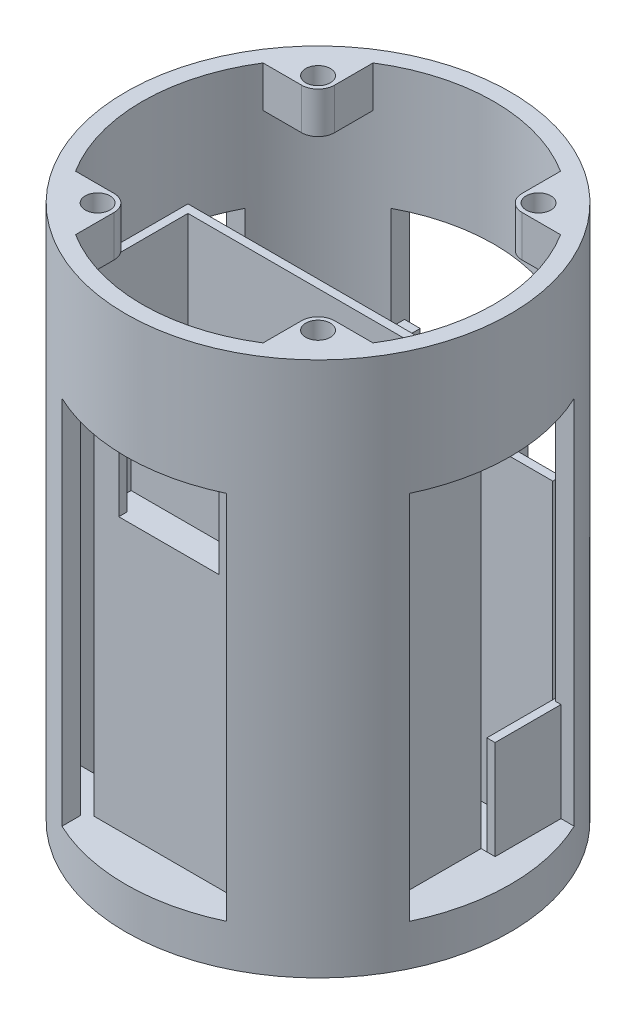
SolidWorks part; units mm, degrees
ref_plane "Plan de face" through (0, 0, 0) normal (0, 0, 1) x (1, 0, 0)
ref_plane "Plan de dessus" through (0, 0, 0) normal (0, 1, 0) x (1, 0, 0)
ref_plane "Plan de droite" through (0, 0, 0) normal (1, 0, 0) x (0, 0, -1)
sketch "Esquisse1" plane through (0, 0, 0) normal (0, 1, 0) x (1, 0, 0)
  circle A0 centre (0, 0) radius 23.35
  dimension "D1" = 46.7
extrude "Boss.-Extru.1" add sketch "Esquisse1" along normal blind 5
sketch "Esquisse2" plane through (0, 5, 0) normal (0, 1, 0) x (1, 0, 0)
  line L1 (-18.5, 10) -> (18.5, 10)
  line L2 (-18.5, 10) -> (-18.5, 2)
  line L3 (-18.5, 2) -> (18.5, 2)
  line L4 (18.5, 10) -> (18.5, 2)
  line L5 (-16.8, 1) -> (16.8, 1)
  line L6 (-16.8, 1) -> (-16.8, -13.6)
  line L7 (-16.8, -13.6) -> (16.8, -13.6)
  line L8 (16.8, 1) -> (16.8, -13.6)
  dimension "D1" = 8
  dimension "D2" = 37
  dimension "D3" = 18.5
  dimension "D4" = 2
  dimension "D5" = 14.6
  dimension "D6" = 33.6
  dimension "D7" = 16.8
  dimension "D8" = 1
extrude "Enlèv. mat.-Extru.4" cut sketch "Esquisse2" against normal blind 3
sketch "Esquisse10" plane through (0, 5, 0) normal (0, 1, 0) x (1, 0, 0)
  circle A0 centre (0, 0) radius 21.35
  circle A1 centre (0, 0) radius 23.35 construction
  circle M2 centre (0, 0) radius 23.35
  line M8 (16.8, 1) -> (16.8, -13.6)
  line M9 (16.8, -13.6) -> (-16.8, -13.6)
  line M10 (-16.8, -13.6) -> (-16.8, 1)
  dimension "D1" = 2
extrude "Boss.-Extru.2" add sketch "Esquisse10" along normal blind 60 contours A0 M2 M8 M9 M10
sketch "Esquisse11" plane through (0, 0, 0) normal (0, 0, 1) x (1, 0, 0)
  line L0 (-23.35, 0) -> (23.35, 0) construction
  line L1 (-10, 5) -> (10, 5)
  line L2 (-10, 5) -> (-10, 50)
  line L3 (-10, 50) -> (10, 50)
  line L4 (10, 5) -> (10, 50)
  line L5 (23.35, 65) -> (-23.35, 65) construction
  dimension "D1" = 5
  dimension "D2" = 15
  dimension "D3" = 10
  dimension "D4" = 20
extrude "Enlèv. mat.-Extru.5" cut sketch "Esquisse11" against normal through all both and the other way through all
sketch "Esquisse12" plane through (0, 0, 0) normal (1, 0, 0) x (0, 0, -1)
  line L0 (23.35, 65) -> (-23.35, 65) construction
  line L1 (-10, 50) -> (10, 50)
  line L2 (-10, 50) -> (-10, 5)
  line L3 (-10, 5) -> (10, 5)
  line L4 (10, 50) -> (10, 5)
  line L5 (-23.35, 0) -> (23.35, 0) construction
  dimension "D1" = 20
  dimension "D2" = 15
  dimension "D3" = 5
  dimension "D4" = 10
extrude "Enlèv. mat.-Extru.6" cut sketch "Esquisse12" against normal through all both and the other way through all
sketch "Esquisse13" plane through (0, 5, 0) normal (0, 1, 0) x (1, 0, 0)
  line L0 (-17.8, 2) -> (-17.8, -11.7891)
  line L1 (-18.5, 2) -> (18.5, 2) construction
  line L2 (17.8, 2) -> (17.8, -11.7891)
  line L3 (-16.8, 1) -> (-16.8, -13.6) construction
  line L4 (16.8, 1) -> (16.8, -13.1751) construction
  line L5 (-16.4579, -13.6) -> (16.4579, -13.6) construction
  line L6 (-8.1, -14.6) -> (8.1, -14.6)
  line L7 (-8.1, -14.6) -> (-8.1, -17.1)
  line L8 (-8.1, -17.1) -> (8.1, -17.1)
  line L9 (8.1, -14.6) -> (8.1, -17.1)
  line L10 (-9.1, -13.6) -> (9.1, -13.6)
  line L11 (-9.1, -13.6) -> (-9.1, -18.1)
  line L12 (-9.1, -18.1) -> (9.1, -18.1)
  line L13 (9.1, -13.6) -> (9.1, -18.1)
  arc A0 (-18.8633, -10) -> (-16.8, -13.1751) centre (0, 0) ccw construction
  arc A1 (16.8, -13.1751) -> (18.8633, -10) centre (0, 0) ccw construction
  point P26 (9.1, -15.85)
  point P27 (8.1, -15.85)
  line M14 (18.5, 2) -> (-18.5, 2)
  arc M15 (16.8, -13.1751) -> (18.8633, -10) centre (0, 0) ccw
  arc M27 (-18.8633, -10) -> (-16.8, -13.1751) centre (0, 0) ccw
  line M28 (-16.8, -13.1751) -> (-16.8, 1)
  line M29 (-16.8, 1) -> (16.8, 1)
  line M30 (16.8, 1) -> (16.8, -13.1751)
  dimension "D1" = 1
  dimension "D2" = 1
  dimension "D3" = 1
  dimension "D4" = 1
  dimension "D5" = 1
  dimension "D6" = 1
  dimension "D7" = 2.5
  dimension "D8" = 16.2
  dimension "D9" = 7.7
  dimension "D10" = 7.7
extrude "Boss.-Extru.4" add sketch "Esquisse13" along normal blind 50 contours L2 L0 M14 M27 M28 M29 M30 M15 | L13 L10 L11 L12 L6 L9 L8 L7 | L9 L6 L7 L8
sketch "Esquisse15" plane through (0, 55, 0) normal (0, 1, 0) x (1, 0, 0)
  line L0 (-16.8, -13.6) -> (16.8, -13.6) construction
  line L1 (-8.1, -14.6) -> (8.1, -14.6)
  line L2 (-8.1, -14.6) -> (-8.1, -17.1)
  line L3 (-8.1, -17.1) -> (-6.1, -17.1)
  line L4 (8.1, -14.6) -> (8.1, -17.1)
  line L5 (9.1, -13.6) -> (9.1, -18.1) construction
  line L6 (-9.1, -13.6) -> (-9.1, -18.1) construction
  line L7 (-6.1, -17.1) -> (-6.1, -18.1)
  line L8 (-9.1, -18.1) -> (9.1, -18.1) construction
  line L9 (6.1, -17.1) -> (6.1, -18.1)
  line L10 (6.1, -17.1) -> (8.1, -17.1)
  line M10 (-9.1, -18.1) -> (9.1, -18.1)
  dimension "D1" = 1
  dimension "D2" = 1
  dimension "D3" = 2.5
  dimension "D4" = 1
  dimension "D5" = 2
  dimension "D6" = 2
extrude "Enlèv. mat.-Extru.7" cut sketch "Esquisse15" against normal blind 17 and the other way through all contours L9 L10 L4 L1 L2 L3 L7 M10
sketch "Esquisse16" plane through (0, 5, 0) normal (0, 1, 0) x (1, 0, 0)
  line L0 (-18.5, 10) -> (18.5, 10) construction
  line L1 (-7.5, 18) -> (7.5, 18)
  line L2 (-7.5, 18) -> (-7.5, 13)
  line L3 (-7.5, 13) -> (7.5, 13)
  line L4 (7.5, 18) -> (7.5, 13)
  dimension "D1" = 5
  dimension "D2" = 15
  dimension "D3" = 7.5
  dimension "D4" = 3
extrude "Boss.-Extru.5" add sketch "Esquisse16" along normal blind 20 contours L4 L1 L2 L3
sketch "Esquisse17" plane through (0, 25, 0) normal (0, 1, 0) x (1, 0, 0)
  line L0 (-0.6, 18) -> (-0.6, 17)
  line L1 (-7.5, 18) -> (7.5, 18) construction
  line L2 (-0.6, 17) -> (5.6, 17)
  line L3 (5.6, 17) -> (5.6, 14)
  line L4 (5.6, 14) -> (-5.6, 14)
  line L5 (-5.6, 14) -> (-5.6, 16.7584)
  line L6 (-5.6, 18) -> (-5.6, 16.7584)
  line L7 (-7.5, 18) -> (7.5, 18) construction
  line L8 (-5.6, 18) -> (-0.6, 18)
  line L9 (-7.5, 13) -> (7.5, 13) construction
  line L10 (7.5, 18) -> (7.5, 13) construction
  line M5 (7.5, 13) -> (7.5, 18)
  line M6 (7.5, 18) -> (-7.5, 18)
  line M7 (-7.5, 18) -> (-7.5, 13)
  line M8 (-7.5, 13) -> (7.5, 13)
  dimension "D1" = 5
  dimension "D2" = 3
  dimension "D3" = 11.2
  dimension "D4" = 1
  dimension "D5" = 1.9
extrude "Boss.-Extru.6" add sketch "Esquisse17" along normal blind 15 contours L6 L0 L2 L3 L4 L5 M6 M7 M8 M5
sketch "Esquisse18" plane through (0, 65, 0) normal (0, 1, 0) x (1, 0, 0)
  line L0 (-11.3859, 20.3859) -> (-11.3859, 13.3859)
  line L1 (-13.3859, 11.3859) -> (-20.3859, 11.3859)
  line L2 (11.3859, 13.3859) -> (11.3859, 20.3859)
  line L3 (20.3859, 11.3859) -> (13.3859, 11.3859)
  line L4 (13.3859, -11.3859) -> (20.3859, -11.3859)
  line L5 (11.3859, -20.3859) -> (11.3859, -13.3859)
  line L6 (-11.3859, -13.3859) -> (-11.3859, -20.3859)
  line L7 (-20.3859, -11.3859) -> (-13.3859, -11.3859)
  circle A0 centre (0, 0) radius 23.35
  circle A2 centre (-13.3859, 13.3859) radius 1.5
  arc A3 (-11.3859, 13.3859) -> (-13.3859, 11.3859) centre (-13.3859, 13.3859) cw
  arc A5 (13.3859, 11.3859) -> (11.3859, 13.3859) centre (13.3859, 13.3859) cw
  circle A6 centre (13.3859, 13.3859) radius 1.5
  arc A8 (11.3859, -13.3859) -> (13.3859, -11.3859) centre (13.3859, -13.3859) cw
  circle A9 centre (13.3859, -13.3859) radius 1.5
  arc A10 (-13.3859, -11.3859) -> (-11.3859, -13.3859) centre (-13.3859, -13.3859) cw
  circle A11 centre (-13.3859, -13.3859) radius 1.5
  arc M3 (-16.8, -13.1751) -> (16.8, -13.1751) centre (0, 0) cw
  line M4 (16.8, -13.1751) -> (16.8, -13.6)
  line M5 (16.8, -13.6) -> (16.4579, -13.6)
  arc M6 (16.4579, -13.6) -> (-16.4579, -13.6) centre (0, 0) cw
  line M7 (-16.4579, -13.6) -> (-16.8, -13.6)
  line M8 (-16.8, -13.6) -> (-16.8, -13.1751)
  dimension "D1" = 2
  dimension "D2" = 4
  dimension "D4" = 46.7
  dimension "D7" = 3
  dimension "D5" = 7
  dimension "D6" = 7
  dimension "D8" = 2
  dimension "D9" = 2
extrude "Boss.-Extru.7" add sketch "Esquisse18" against normal blind 5 contours A3 L0 L1 M3 | A5 L3 L2 A6 M3 | A8 L5 L4 A9 M6 M5 M4 M3 | A10 L7 L6 A11 M3 M8 M7 M6
sketch "Esquisse33" plane through (0, 5, 0) normal (0, 1, 0) x (1, 0, 0)
  line L0 (-18.5, 2) -> (-19.5, 2)
  line L1 (-19.5, 2) -> (-19.5, 8.6932)
  line L2 (18.5, 2) -> (19.5, 2)
  line L3 (19.5, 2) -> (19.5, 8.6932)
  line L4 (-18.2982, 11) -> (18.2982, 11)
  line L5 (-18.5, 10) -> (18.5, 10) construction
  line L6 (18.5, 10) -> (18.5, 2) construction
  line L7 (-18.5, 10) -> (-18.5, 2) construction
  line L8 (-19.5, 8.6932) -> (-19.5, 11)
  line L9 (-19.5, 11) -> (-18.2982, 11)
  line L10 (19.5, 8.6932) -> (19.5, 11)
  line L11 (19.5, 11) -> (18.129, 11)
  arc A0 (-17.2469, 12.5844) -> (-16.8, -13.1751) centre (0, 0) ccw construction
  arc A1 (16.8, -13.1751) -> (17.2469, 12.5844) centre (0, 0) ccw construction
  arc A2 (18.8633, 10) -> (10, 18.8633) centre (0, 0) ccw construction
  line M13 (21.1003, 10) -> (18.8633, 10)
  arc M14 (18.8633, 10) -> (10, 18.8633) centre (0, 0) ccw
  arc M18 (-10, 18.8633) -> (-18.8633, 10) centre (0, 0) ccw
  line M19 (-18.8633, 10) -> (-21.1003, 10)
  line M25 (-18.5, 2) -> (-18.5, 10)
  line M26 (-18.5, 10) -> (18.5, 10)
  line M27 (18.5, 10) -> (18.5, 2)
  dimension "D1" = 1
  dimension "D2" = 1
  dimension "D3" = 1
extrude "Boss.-Extru.8" add sketch "Esquisse33" along normal blind 12 contours L3 L10 L4 L8 L1 L0 L2 M13 M14 M18 M19 M25 M26 M27
sketch "Esquisse34" plane through (0, 17, 0) normal (0, 1, 0) x (1, 0, 0)
  line L0 (18.5, 10) -> (18.5, 10.657)
  arc A0 (18.8633, 10) -> (18.2982, 11) centre (0, 0) ccw construction
  arc M3 (18.8633, 10) -> (18.2982, 11) centre (0, 0) ccw
  line M4 (18.2982, 11) -> (-18.2982, 11)
  arc M5 (-18.2982, 11) -> (-18.8633, 10) centre (0, 0) ccw
  line M6 (-18.8633, 10) -> (-19.5, 10)
  line M7 (-19.5, 10) -> (-19.5, 2)
  line M8 (-19.5, 2) -> (-18.5, 2)
  line M9 (-18.5, 2) -> (-18.5, 10)
  line M10 (-18.5, 10) -> (18.5, 10)
extrude "Boss.-Extru.9" add sketch "Esquisse34" along normal blind 23 contours L0 M10 M3 M4 M5 M6 M7 M8 M9
